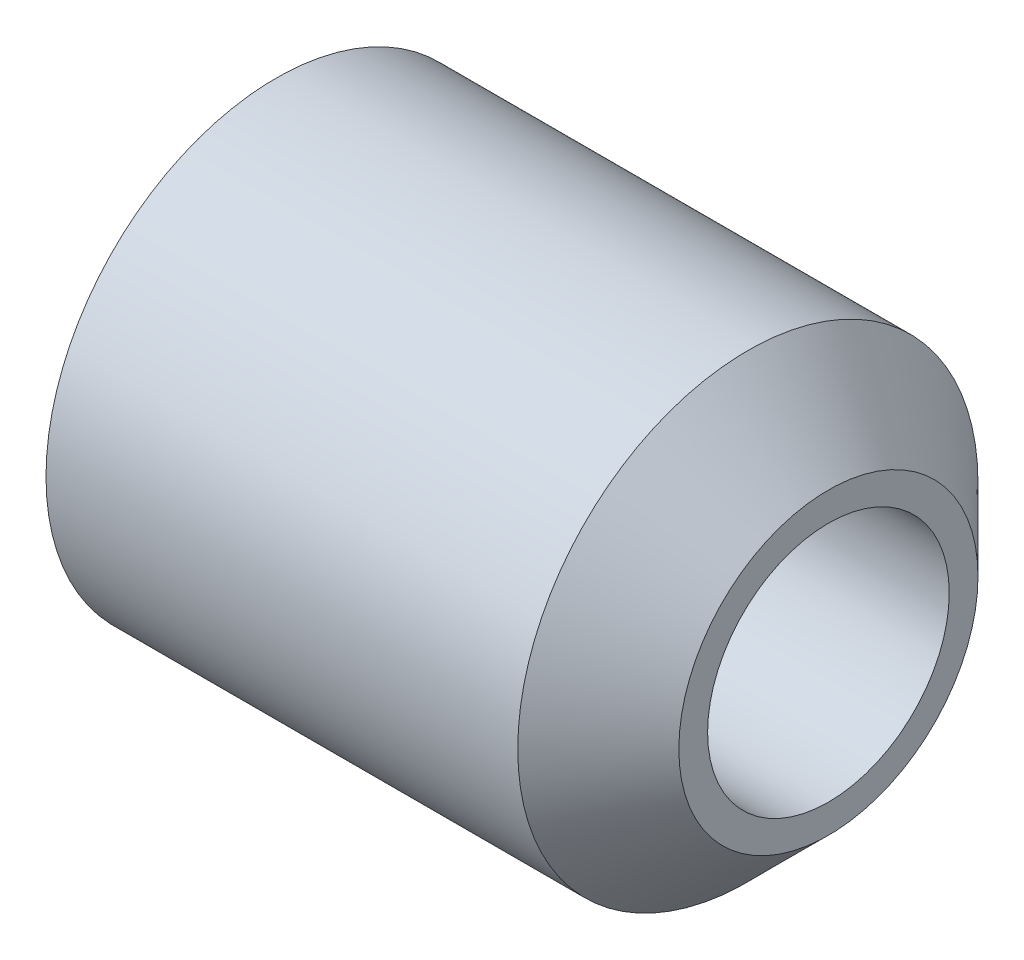
SolidWorks part; units mm, degrees
ref_plane "Front Plane" through (0, 0, 0) normal (0, 0, 1) x (1, 0, 0)
ref_plane "Top Plane" through (0, 0, 0) normal (0, 1, 0) x (1, 0, 0)
ref_plane "Right Plane" through (0, 0, 0) normal (1, 0, 0) x (0, 0, -1)
sketch "Sketch2" plane through (0, 0, 0) normal (1, 0, 0) x (0, 0, -1)
  circle A0 centre (0, 0) radius 5.25
  circle A1 centre (0, 0) radius 10
  dimension "D1" = 10.5
  dimension "D2" = 20
extrude "Boss-Extrude1" add sketch "Sketch2" along normal blind 24
chamfer "Chamfer1" distance 3.5 angle 45 1 edges at (24, 0, -10)
